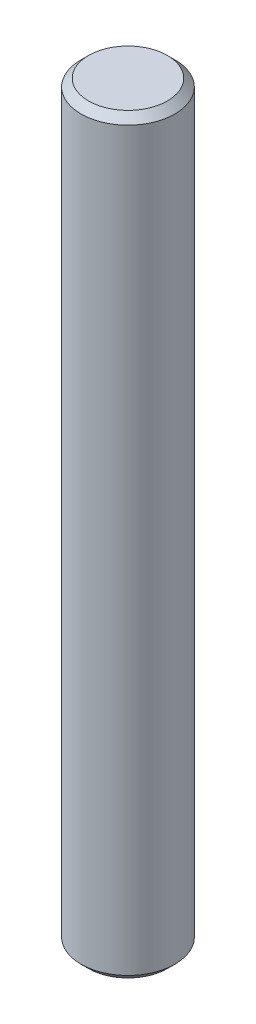
SolidWorks part; units mm, degrees
ref_plane "Front Plane" through (0, 0, 0) normal (0, 0, 1) x (1, 0, 0)
ref_plane "Top Plane" through (0, 0, 0) normal (0, 1, 0) x (1, 0, 0)
ref_plane "Right Plane" through (0, 0, 0) normal (1, 0, 0) x (0, 0, -1)
sketch "Sketch2" plane through (0, 0, 0) normal (0, 1, 0) x (1, 0, 0)
  circle A0 centre (0, 0) radius 12.5
  dimension "D1" = 25
extrude "Boss-Extrude1" add sketch "Sketch2" along normal blind 200
chamfer "Chamfer1" distance 2 angle 45 2 edges at (0, 0, 12.5) (0, 200, 12.5)
